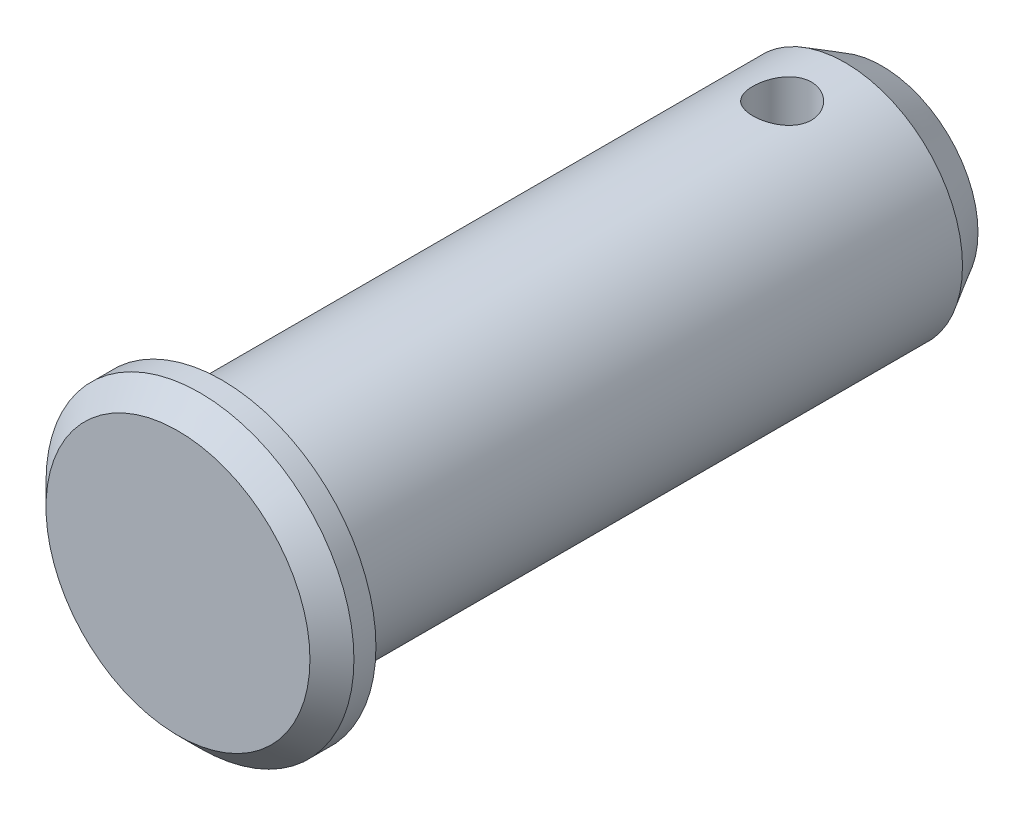
SolidWorks part; units mm, degrees
material "1.0545 (S355N)"
ref_plane "Płaszczyzna przednia" through (0, 0, 0) normal (0, 0, 1) x (1, 0, 0)
ref_plane "Płaszczyzna górna" through (0, 0, 0) normal (0, 1, 0) x (1, 0, 0)
ref_plane "Płaszczyzna prawa" through (0, 0, 0) normal (1, 0, 0) x (0, 0, -1)
sketch "Szkic1" plane through (0, 0, 0) normal (0, 1, 0) x (1, 0, 0)
  line L0 (9, -24) -> (-9, -24)
  line L1 (-10.5, -22.5) -> (-10.5, -21)
  line L2 (-10.5, -21) -> (-8, -21)
  line L3 (-8, -21) -> (-8, 21.5)
  line L4 (-6.5566, 24) -> (6.5566, 24)
  line L5 (8, 21.5) -> (8, -21)
  line L6 (8, -21) -> (10.5, -21)
  line L7 (10.5, -21) -> (10.5, -22.5)
  line L8 (10.5, -22.5) -> (9, -24)
  line L9 (-9, -24) -> (-10.5, -22.5)
  line L10 (6.5566, 24) -> (8, 21.5)
  line L11 (-8, 21.5) -> (-6.5566, 24)
  line L12 (0, -24) -> (0, 24)
  point P0 (10.5, -24)
  point P1 (-10.5, -24)
  point P5 (-8, 24)
  point P6 (8, 24)
  point P7 (0, 0)
  point P17 (0, 24)
  point P19 (0, -24)
  dimension "D1" = 21
  dimension "D2" = 16
  dimension "D3" = 2.5
  dimension "D4" = 30
  dimension "D8" = 30
  dimension "D9" = 45
  dimension "D10" = 3
revolve "Obrót1" add sketch "Szkic1" angle 360 about L12
sketch "Szkic2" plane through (0, 0, 0) normal (0, 1, 0) x (1, 0, 0)
  line L0 (8, -21) -> (-8, -21) construction
  circle A0 centre (0, 17.2) radius 2
  dimension "D2" = 4
  dimension "D1" = 38.2
extrude "Wytnij-wyciągnięcie1" cut sketch "Szkic2" against normal through all both and the other way through all contours A0
